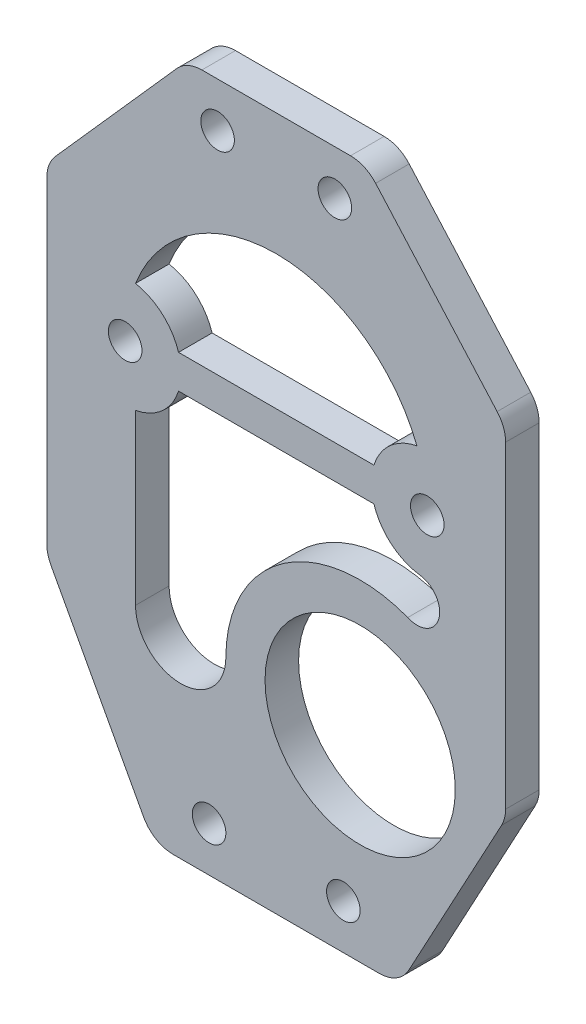
SolidWorks part; units mm, degrees
ref_plane "Front Plane" through (0, 0, 0) normal (0, 0, 1) x (1, 0, 0)
ref_plane "Top Plane" through (0, 0, 0) normal (0, 1, 0) x (1, 0, 0)
ref_plane "Right Plane" through (0, 0, 0) normal (1, 0, 0) x (0, 0, -1)
sketch "Sketch2" plane through (0, 0, 0) normal (0, 0, 1) x (1, 0, 0)
  line L0 (6.5495, -24.6335) -> (6.5495, 37.3665) construction
  line L1 (17.5495, -24.6335) -> (-4.4505, -24.6335)
  line L2 (-4.4505, -24.6335) -> (-13.9505, -7.0338)
  line L3 (-13.9505, -7.0338) -> (-13.9505, 23.2662)
  line L4 (-13.9505, 23.2662) -> (-1.4403, 37.3665)
  line L5 (-1.4403, 37.3665) -> (14.5393, 37.3665)
  line L6 (17.5495, -24.6335) -> (27.0495, -7.0338)
  line L7 (27.0495, -7.0338) -> (27.0495, 23.2662)
  line L8 (27.0495, 23.2662) -> (14.5393, 37.3665)
  line L9 (14.0495, -7.0338) -> (27.0495, -7.0338) construction
  line L10 (-6.9505, 12.9662) -> (20.0495, 12.9662) construction
  line L11 (-6.0246, 8.0527) -> (-6.0246, -7.0338)
  line L12 (-2.1808, 14.4662) -> (15.2798, 14.4662) construction
  line L13 (-2.1808, 14.4662) -> (-2.1808, 11.4662) construction
  line L14 (-2.1808, 11.4662) -> (15.2798, 11.4662) construction
  line L15 (15.2798, 14.4662) -> (15.2798, 11.4662) construction
  line L16 (-2.1808, 14.4662) -> (15.2798, 11.4662) construction
  line L17 (-2.1808, 11.4662) -> (15.2798, 14.4662) construction
  line L18 (-2.1808, 11.4662) -> (15.2798, 11.4662)
  line L19 (-2.1808, 14.4662) -> (15.2798, 14.4662)
  circle A0 centre (1.3097, 33.3665) radius 1.5
  circle A1 centre (-6.9505, 12.9662) radius 1.5
  circle A2 centre (0.5495, -20.6335) radius 1.5
  circle A3 centre (12.5495, -20.6335) radius 1.5
  circle A4 centre (20.0495, 12.9662) radius 1.5
  circle A5 centre (11.7893, 33.3665) radius 1.5
  circle A6 centre (14.0495, -7.0338) radius 8.5
  circle A7 centre (20.0495, 12.9662) radius 5 construction
  circle A8 centre (-6.9505, 12.9662) radius 5 construction
  circle A9 centre (14.0495, -7.0338) radius 12 construction
  arc A10 (-6.0246, 17.8797) -> (19.1236, 17.8797) centre (6.5495, 12.9662) cw
  arc A11 (-6.0246, 17.8797) -> (-2.1808, 14.4662) centre (-6.9505, 12.9662) cw
  arc A12 (15.2798, 14.4662) -> (19.1236, 17.8797) centre (20.0495, 12.9662) cw
  arc A13 (-2.1808, 11.4662) -> (-6.0246, 8.0527) centre (-6.9505, 12.9662) cw
  arc A14 (15.2798, 11.4662) -> (19.4052, 8.0079) centre (20.0495, 12.9662) ccw
  arc A15 (19.4052, 8.0079) -> (18.3047, 4.1864) centre (19.146, 6.0133) cw
  arc A16 (18.3047, 4.1864) -> (2.0495, -7.0338) centre (14.0495, -7.0338) ccw
  arc A17 (-6.0246, -7.0338) -> (2.0495, -7.0338) centre (-1.9875, -7.0338) ccw
  point P30 (6.5587, 25.591)
  dimension "D13" = 17
  dimension "D19" = 3
  dimension "D18" = 13.5
  dimension "D1" = 62
  dimension "D2" = 11
  dimension "D3" = 20
  dimension "D4" = 30.3
  dimension "D5" = 18.85
  dimension "D6" = 20.5
  dimension "D7" = 4
  dimension "D8" = 2.75
  dimension "D9" = 10.3
  dimension "D10" = 7
  dimension "D11" = 6
  dimension "D12" = 4
  dimension "D14" = 13
  dimension "D20" = 3
  dimension "D15" = 3.5
  dimension "D16" = 3.5
  dimension "D17" = 3.5
extrude "Boss-Extrude2" add sketch "Sketch2" along normal blind 3
fillet "Fillet1" radius 3 8 edges at (-4.4505, -24.6335, 1.5) (17.5495, -24.6335, 1.5) (27.0495, -7.0338, 1.5) (27.0495, 23.2662, 1.5) (14.5393, 37.3665, 1.5) (-1.4403, 37.3665, 1.5) (-13.9505, 23.2662, 1.5) (-13.9505, -7.0338, 1.5)
